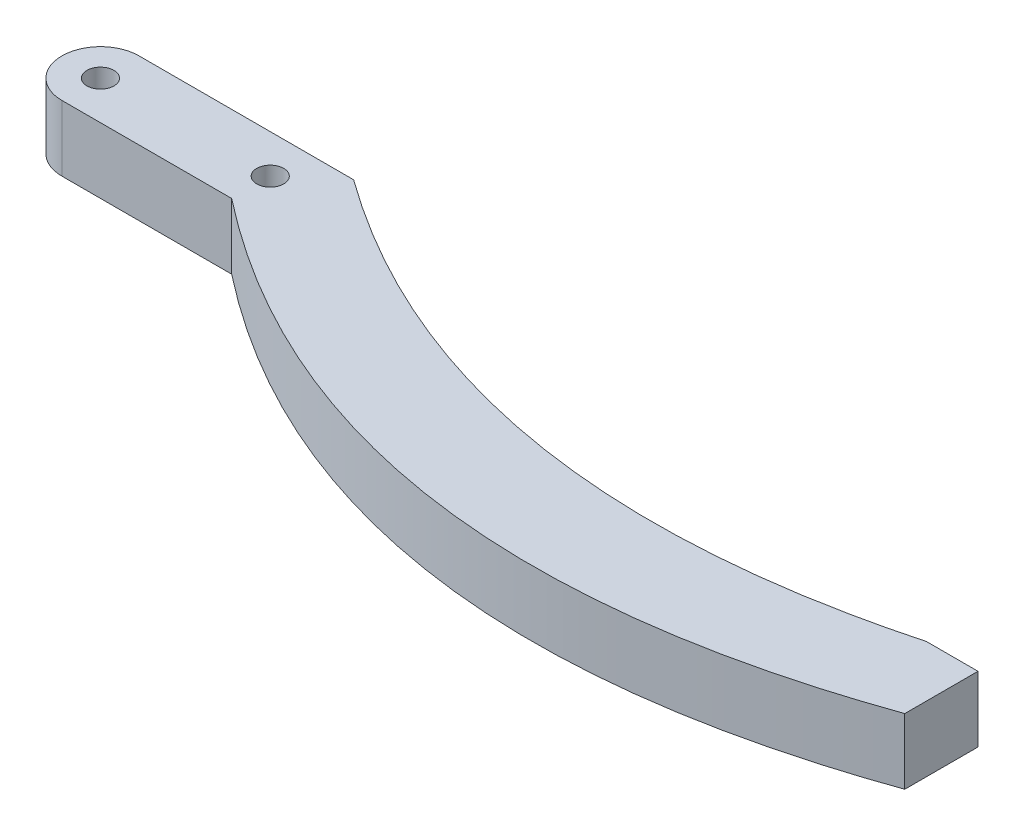
SolidWorks part; units mm, degrees
ref_plane "Alzado" through (0, 0, 0) normal (0, 0, 1) x (1, 0, 0)
ref_plane "Planta" through (0, 0, 0) normal (0, 1, 0) x (1, 0, 0)
ref_plane "Vista lateral" through (0, 0, 0) normal (1, 0, 0) x (0, 0, -1)
sketch "Croquis2" plane through (0, 0, 0) normal (0, 1, 0) x (1, 0, 0)
  line L0 (0, 0) -> (-22, 0) construction
  line L1 (0, -5) -> (-22, -5)
  line L2 (0, 5) -> (-22, 5)
  line L13 (5.809, 5) -> (-0.7631, 5)
  line L14 (94.7483, -9.7067) -> (101.4326, -9.7067)
  line L15 (101.4326, -9.7067) -> (101.4326, -19.1999)
  arc A1 (-22, 5) -> (-22, -5) centre (-22, 0) ccw
  circle A4 centre (-22, 0) radius 1.75
  circle A5 centre (0, 0) radius 1.75
  spline S0 degree 2 poles (5.809, 5) (44.7036, -23.1482) (94.7483, -9.7067) knots 0 0 0 1 1 1
  spline S1 degree 2 poles (0, -5) (44.0607, -39.5752) (101.4326, -19.1999) knots 0 0 0 1 1 1
  point P3 (-11, 0)
  point P9 (81.016, 41.0564)
  dimension "D2" = 3.5
  dimension "D4" = 3.5
  dimension "D5" = 10
  dimension "D6" = 22
extrude "Saliente-Extruir1" add sketch "Croquis2" along normal blind 8.5
